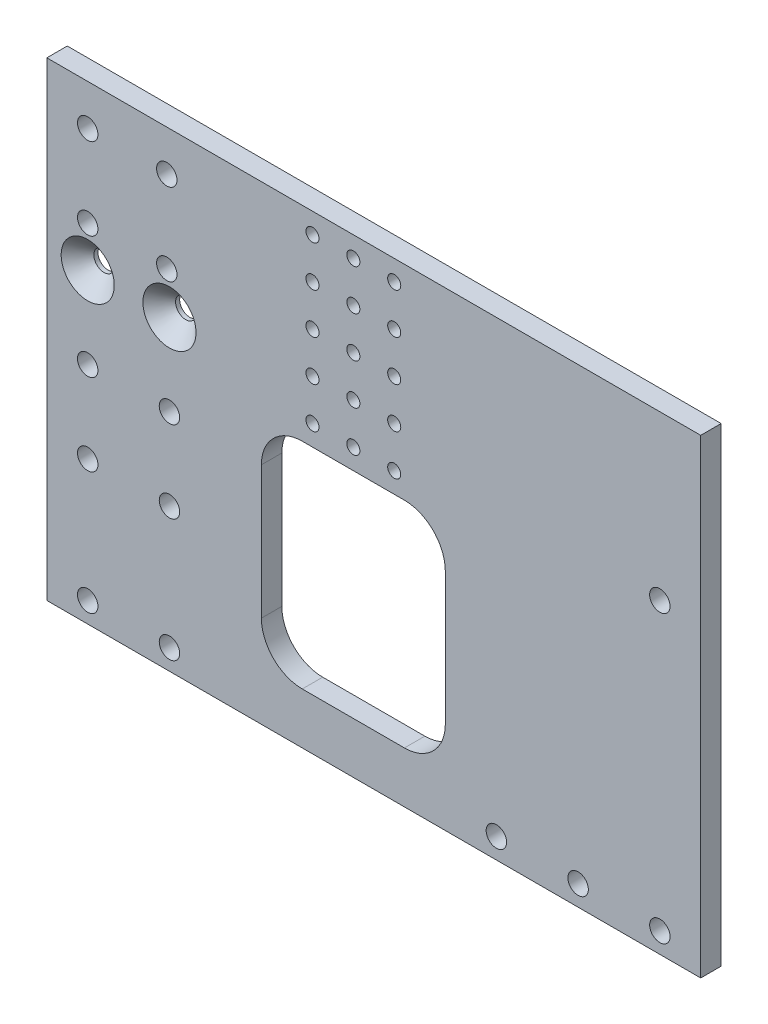
SolidWorks part; units mm, degrees
ref_plane "Front Plane" through (0, 0, 0) normal (0, 0, 1) x (1, 0, 0)
ref_plane "Top Plane" through (0, 0, 0) normal (0, 1, 0) x (1, 0, 0)
ref_plane "Right Plane" through (0, 0, 0) normal (1, 0, 0) x (0, 0, -1)
sketch "Sketch1" plane through (0, 0, 0) normal (0, 0, 1) x (1, 0, 0)
  line L1 (0, 0) -> (203.2, 0)
  line L2 (0, 0) -> (0, 146.05)
  line L3 (0, 146.05) -> (203.2, 146.05)
  line L4 (203.2, 0) -> (203.2, 146.05)
  dimension "D1" = 146.05
  dimension "D2" = 203.2
extrude "Boss-Extrude1" add sketch "Sketch1" along normal blind 6.35
sketch "Sketch2" plane through (0, 0, 6.35) normal (0, 0, 1) x (1, 0, 0)
  line L0 (0, 0) -> (203.2, 0) construction
  line L1 (12.7, 6.35) -> (38.1, 6.35) construction
  line L2 (12.7, 6.35) -> (12.7, 95.25) construction
  line L3 (12.7, 95.25) -> (38.1, 95.25) construction
  line L4 (38.1, 6.35) -> (38.1, 95.25) construction
  line L5 (0, 146.05) -> (0, 0) construction
  line L6 (38.1, 95.25) -> (190.5, 95.25) construction
  line L7 (38.1, 6.35) -> (190.5, 6.35) construction
  line L8 (190.5, 6.35) -> (190.5, 95.25) construction
  line L9 (203.2, 0) -> (203.2, 146.05) construction
  line L10 (12.7, 120.65) -> (12.7, 111.0791) construction
  line L11 (12.7, 95.25) -> (12.7, 69.85) construction
  line L12 (12.7, 104.7291) -> (12.7, 95.25) construction
  line L23 (12.7, 120.65) -> (12.7, 111.0791)
  line L24 (203.2, 146.05) -> (0, 146.05) construction
  circle A0 centre (12.7, 6.35) radius 3.175
  circle A1 centre (38.1, 6.35) radius 3.175
  circle A2 centre (12.7, 95.25) radius 3.175
  circle A3 centre (38.1, 95.25) radius 3.175
  circle A4 centre (190.5, 95.25) radius 3.175
  circle A5 centre (190.5, 6.35) radius 3.175
  circle A6 centre (12.7, 69.85) radius 3.175
  circle A7 centre (38.1, 69.85) radius 3.175
  circle A8 centre (12.7, 44.45) radius 3.175
  circle A9 centre (38.1, 44.45) radius 3.175
  circle A12 centre (165.1, 6.35) radius 3.175
  circle A13 centre (139.7, 6.35) radius 3.175
  circle A14 centre (37.2703, 133.35) radius 3.175
  circle A15 centre (37.2703, 107.9041) radius 3.175
  circle A16 centre (12.7, 107.9041) radius 3.175
  circle A17 centre (12.7, 133.35) radius 3.175
  dimension "D2" = 6.35
  dimension "D13" = 6.35
  dimension "D14" = 6.35
  dimension "D15" = 6.35
  dimension "D16" = 6.35
  dimension "D18" = 12.7
  dimension "D19" = 25.4459
  dimension "D20" = 37.2703
  dimension "D21" = 24.5703
  dimension "D22" = 12.7
  dimension "D23" = 25.4
  dimension "D1" = 6.35
  dimension "D3" = 12.7
  dimension "D4" = 88.9
  dimension "D5" = 25.4
  dimension "D6" = 12.7
  dimension "D9" = 25.4
  dimension "D10" = 25.4
  dimension "D11" = 25.4
  dimension "D8" = 25.4459
  dimension "D12" = 12.7
  dimension "D17" = 37.2703
  dimension "D7" = 3
extrude "Cut-Extrude1" cut sketch "Sketch2" against normal through all both and the other way through all contours A17 | A14 | A16 | A15 | A2 | A3 | A6 | A7 | A8 | A9 | A0 | A1 | A13 | A12 | A5 | A4
sketch "Sketch3" plane through (0, 0, 6.35) normal (0, 0, 1) x (1, 0, 0)
  line L0 (82.55, 139.7) -> (107.95, 139.7) construction
  line L1 (82.55, 139.7) -> (82.55, 127) construction
  line L2 (82.55, 127) -> (107.95, 127) construction
  line L3 (107.95, 127) -> (107.95, 139.7) construction
  line L4 (0, 146.05) -> (0, 0) construction
  line L6 (203.2, 146.05) -> (0, 146.05) construction
  circle A0 centre (95.25, 139.7) radius 2.032
  circle A1 centre (107.95, 139.7) radius 2.032
  circle A2 centre (82.55, 139.7) radius 2.032
  circle A3 centre (107.95, 127) radius 2.032
  circle A4 centre (95.25, 127) radius 2.032
  circle A5 centre (82.55, 127) radius 2.032
  circle A6 centre (107.95, 114.3) radius 2.032
  circle A7 centre (95.25, 114.3) radius 2.032
  circle A8 centre (82.55, 114.3) radius 2.032
  circle A9 centre (107.95, 101.6) radius 2.032
  circle A10 centre (95.25, 101.6) radius 2.032
  circle A11 centre (82.55, 101.6) radius 2.032
  circle A12 centre (107.95, 88.9) radius 2.032
  circle A13 centre (95.25, 88.9) radius 2.032
  circle A14 centre (82.55, 88.9) radius 2.032
  dimension "D4" = 4.064
  dimension "D1" = 25.4
  dimension "D2" = 95.25
  dimension "D3" = 6.35
  dimension "D5" = 12.7
  dimension "D6" = 5
extrude "Cut-Extrude2" cut sketch "Sketch3" against normal through all both and the other way through all
sketch "Sketch4" plane through (0, 0, 6.35) normal (0, 0, 1) x (1, 0, 0)
  line L1 (66.675, 82.55) -> (123.825, 82.55)
  line L2 (66.675, 82.55) -> (66.675, 15.875)
  line L3 (66.675, 15.875) -> (123.825, 15.875)
  line L4 (123.825, 82.55) -> (123.825, 15.875)
  line L5 (95.25, 101.6) -> (95.25, 82.55) construction
  circle A0 centre (107.95, 88.9) radius 2.032 construction
  dimension "D2" = 6.35
  dimension "D1" = 57.15
  dimension "D3" = 66.675
extrude "Cut-Extrude3" cut sketch "Sketch4" against normal through all both and the other way through all
fillet "Fillet1" radius 12.7 4 edges at (123.825, 82.55, 3.175) (66.675, 82.55, 3.175) (123.825, 15.875, 3.175) (66.675, 15.875, 3.175)
chamfer "Chamfer1" distance 5.08 angle 45 2 edges at (34.925, 95.25, 6.35) (9.525, 95.25, 6.35)
